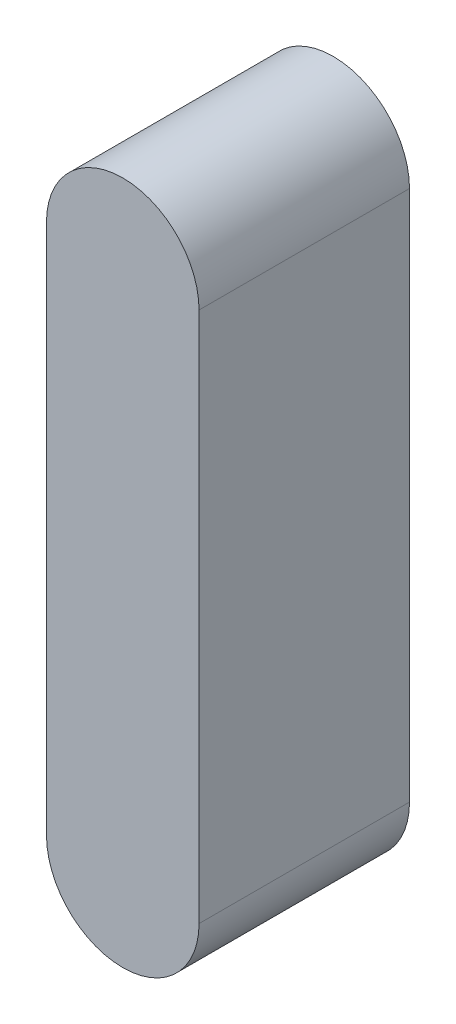
SolidWorks part; units mm, degrees
ref_plane "Front Plane" through (0, 0, 0) normal (0, 0, 1) x (1, 0, 0)
ref_plane "Top Plane" through (0, 0, 0) normal (0, 1, 0) x (1, 0, 0)
ref_plane "Right Plane" through (0, 0, 0) normal (1, 0, 0) x (0, 0, -1)
sketch "Sketch1" plane through (0, 0, 0) normal (0, 0, 1) x (1, 0, 0)
  line L0 (0, -5.05) -> (0, 5.05) construction
  line L1 (-1.45, -5.05) -> (-1.45, 5.05)
  line L2 (1.45, -5.05) -> (1.45, 5.05)
  line L3 (0, 6.5) -> (0, -6.5)
  arc A0 (-1.45, -5.05) -> (1.45, -5.05) centre (0, -5.05) ccw
  arc A1 (1.45, 5.05) -> (-1.45, 5.05) centre (0, 5.05) ccw
  point P2 (0, 0)
  dimension "D1" = 13
  dimension "D2" = 2.9
extrude "Boss-Extrude1" add sketch "Sketch1" along normal blind 4 contours L2 A1 L3 A0 | L3 A1 L1 A0
